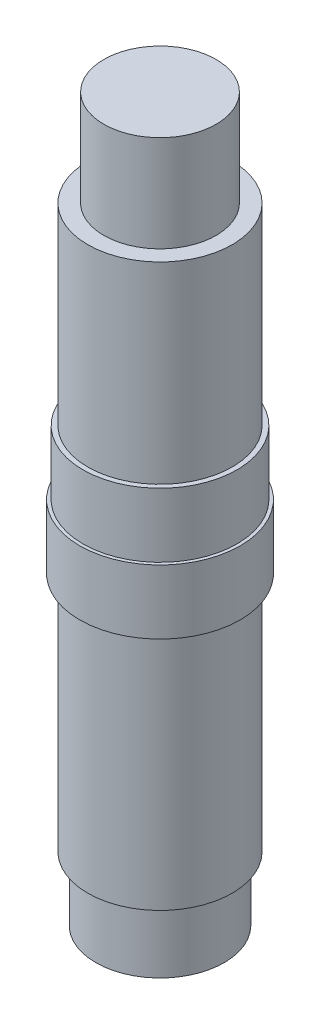
SolidWorks part; units mm, degrees
ref_plane "前视基准面" through (0, 0, 0) normal (0, 0, 1) x (1, 0, 0)
ref_plane "上视基准面" through (0, 0, 0) normal (0, 1, 0) x (1, 0, 0)
ref_plane "右视基准面" through (0, 0, 0) normal (1, 0, 0) x (0, 0, -1)
sketch "草图1" plane through (0, 0, 0) normal (0, 1, 0) x (1, 0, 0)
  circle A0 centre (0, 0) radius 20
extrude "凸台-拉伸1" add sketch "草图1" along normal blind 20
sketch "草图2" plane through (0, 20, 0) normal (0, 1, 0) x (1, 0, 0)
  circle A0 centre (0, 0) radius 22.5
extrude "凸台-拉伸2" add sketch "草图2" along normal blind 75
sketch "草图3" plane through (0, 95, 0) normal (0, 1, 0) x (1, 0, 0)
  circle A0 centre (0, 0) radius 25
extrude "凸台-拉伸3" add sketch "草图3" along normal blind 20
sketch "草图4" plane through (0, 115, 0) normal (0, 1, 0) x (1, 0, 0)
  circle A0 centre (0, 0) radius 24
extrude "凸台-拉伸4" add sketch "草图4" along normal blind 20
sketch "草图5" plane through (0, 135, 0) normal (0, 1, 0) x (1, 0, 0)
  circle A0 centre (0, 0) radius 22.5
extrude "凸台-拉伸5" add sketch "草图5" along normal blind 60
sketch "草图6" plane through (0, 195, 0) normal (0, 1, 0) x (1, 0, 0)
  circle A0 centre (0, 0) radius 17.5
extrude "凸台-拉伸6" add sketch "草图6" along normal blind 30
